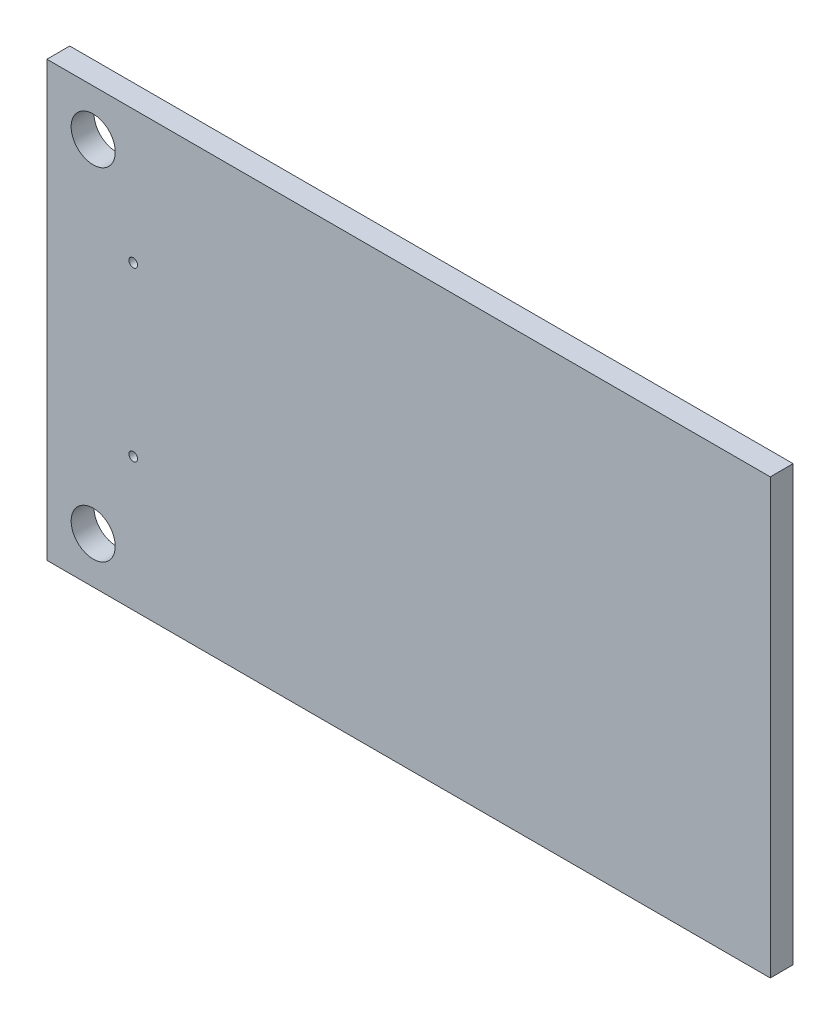
SolidWorks part; units mm, degrees
material "Copper"
ref_plane "Front Plane" through (0, 0, 0) normal (0, 0, 1) x (1, 0, 0)
ref_plane "Top Plane" through (0, 0, 0) normal (0, 1, 0) x (1, 0, 0)
ref_plane "Right Plane" through (0, 0, 0) normal (1, 0, 0) x (0, 0, -1)
sketch "Sketch1" plane through (0, 0, 0) normal (0, 0, 1) x (1, 0, 0)
  line L0 (-21.8, 11.8) -> (-21.8, 15) construction
  line L1 (-25, 15) -> (25, 15)
  line L2 (-25, 15) -> (-25, -15)
  line L3 (-25, -15) -> (25, -15)
  line L4 (25, 15) -> (25, -15)
  line L5 (-25, 15) -> (25, -15) construction
  line L6 (-25, -15) -> (25, 15) construction
  line L7 (-21.8, 11.8) -> (-25, 11.8) construction
  line L8 (-21.8, -11.8) -> (-21.8, -15) construction
  line L9 (-21.8, -11.8) -> (-25, -11.8) construction
  line L10 (-25, 5.8) -> (-19.032, 5.8) construction
  line L11 (-19.032, 5.8) -> (-19.032, 15) construction
  line L12 (-25, -5.8) -> (-19.032, -5.8) construction
  line L13 (-19.032, -5.8) -> (-19.032, -15) construction
  line L14 (-19.032, -5.8) -> (-19.032, 5.8) construction
  line L15 (14.3238, 15) -> (14.3238, 12.319) construction
  line L16 (14.3238, 12.319) -> (25, 12.319) construction
  circle A0 centre (-21.8, 11.8) radius 1.524
  circle A1 centre (-21.8, -11.8) radius 1.524
  circle A2 centre (-19.032, 5.8) radius 0.3
  circle A3 centre (-19.032, -5.8) radius 0.3
  circle A4 centre (14.3238, 12.319) radius 0.4 construction
  point P0 (0, 0)
  dimension "D3" = 3.048
  dimension "D5" = 0.6
  dimension "D1" = 30
  dimension "D2" = 50
  dimension "D4" = 3.2
  dimension "D6" = 9.2
  dimension "D7" = 5.968
  dimension "D8" = 10.6762
  dimension "D9" = 2.681
extrude "Boss-Extrude1" add sketch "Sketch1" along normal blind 1.58
